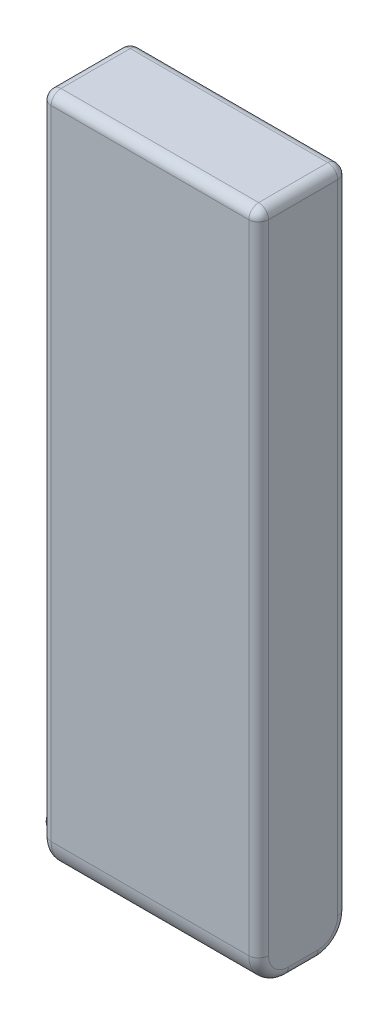
SolidWorks part; units mm, degrees
ref_plane "Front Plane" through (0, 0, 0) normal (1, 0, 0) x (0, 1, 0)
ref_plane "Top Plane" through (0, 0, 0) normal (0, 0, 1) x (0, 1, 0)
ref_plane "Right Plane" through (0, 0, 0) normal (0, 1, 0) x (-1, 0, 0)
sketch "Sketch1" plane through (0, 0, 0) normal (0, 0, 1) x (0, 1, 0)
  line L1 (-68.5, -22) -> (68.5, -22)
  line L2 (-68.5, -22) -> (-68.5, 22)
  line L3 (-68.5, 22) -> (68.5, 22)
  line L4 (68.5, -22) -> (68.5, 22)
  line L5 (-68.5, -22) -> (68.5, 22) construction
  line L6 (-68.5, 22) -> (68.5, -22) construction
  point P0 (0, 0)
  dimension "D1" = 137
  dimension "D2" = 44
extrude "Boss-Extrude1" add sketch "Sketch1" along normal blind 18
fillet "Fillet1" radius 6 2 edges at (0, -68.5, 0) (0, -68.5, 18)
fillet "Fillet2" radius 2 14 edges at (22, 3, 0) (22, -66.7426, 1.7574) (22, -68.5, 9) (22, -66.7426, 16.2426) (-22, 3, 0) (-22, -66.7426, 1.7574) (-22, -68.5, 9) (-22, -66.7426, 16.2426) (0, 68.5, 18) (22, 3, 18) (-22, 3, 18) (22, 68.5, 9) (-22, 68.5, 9) (0, 68.5, 0)
sketch "Sketch2" plane through (-22, 0, 0) normal (-1, 0, 0) x (0, -1, 0)
  line L0 (62.5, 16) -> (62.5, 9) construction
  line L1 (66.5, 9) -> (62.5, 9) construction
  line L2 (66.5, 6) -> (66.5, 12) construction
  line L3 (62.5, 9) -> (62.5, 2) construction
  circle A0 centre (62.5, 12.5) radius 2.5
  circle A1 centre (62.5, 5.5) radius 2.5
  dimension "D1" = 5
  dimension "D2" = 5
extrude "Boss-Extrude2" add sketch "Sketch2" along normal blind 2
